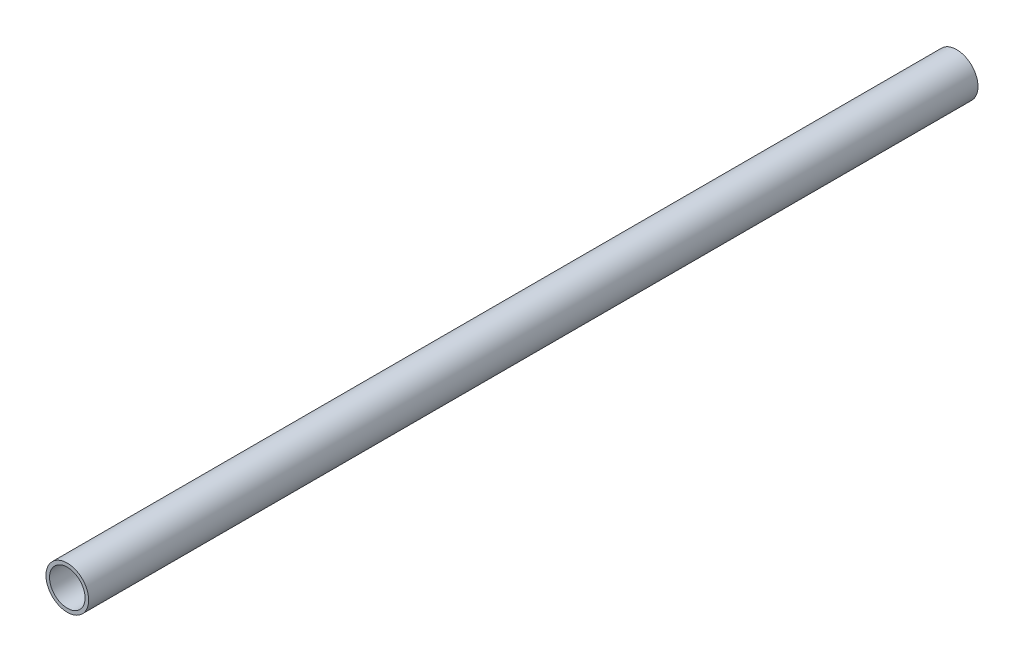
SolidWorks part; units mm, degrees
material "Alliage 1060"
ref_plane "Plan de face" through (0, 0, 0) normal (0, 0, 1) x (1, 0, 0)
ref_plane "Plan de dessus" through (0, 0, 0) normal (0, 1, 0) x (1, 0, 0)
ref_plane "Plan de droite" through (0, 0, 0) normal (1, 0, 0) x (0, 0, -1)
sketch "Esquisse1" plane through (0, 0, 0) normal (0, 0, 1) x (1, 0, 0)
  circle A0 centre (0, 0) radius 12
  circle A1 centre (0, 0) radius 10
  dimension "D1" = 24
  dimension "D2" = 2
extrude "Boss.-Extru.1" add sketch "Esquisse1" along normal blind 500
